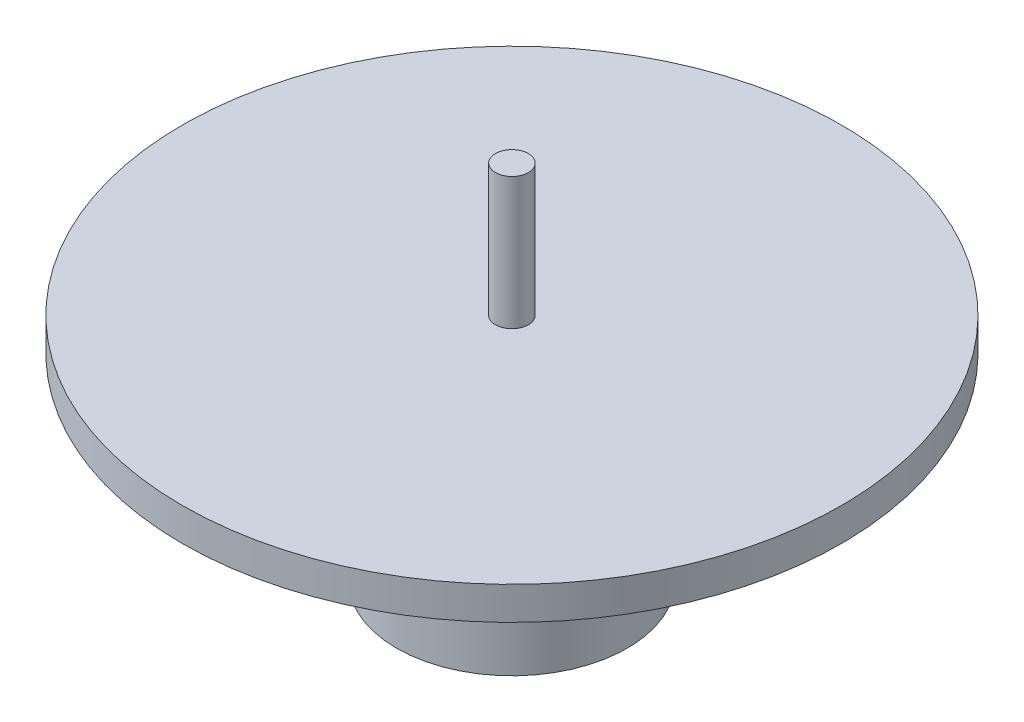
SolidWorks part; units mm, degrees
ref_plane "Plan de face" through (0, 0, 0) normal (0, 0, 1) x (1, 0, 0)
ref_plane "Plan de dessus" through (0, 0, 0) normal (0, 1, 0) x (1, 0, 0)
ref_plane "Plan de droite" through (0, 0, 0) normal (1, 0, 0) x (0, 0, -1)
sketch "Esquisse1" plane through (0, 0, 0) normal (0, 1, 0) x (1, 0, 0)
  circle A0 centre (0, 0) radius 3.5
  dimension "D1" = 7
extrude "Boss.-Extru.1" add sketch "Esquisse1" along normal blind 5
sketch "Esquisse4" plane through (0, 5, 0) normal (0, 1, 0) x (1, 0, 0)
  circle A0 centre (0, 0) radius 5.5
  dimension "D1" = 11
extrude "Boss.-Extru.3" add sketch "Esquisse4" along normal blind 1
sketch "Esquisse5" plane through (0, 6, 0) normal (0, 1, 0) x (1, 0, 0)
  circle A0 centre (0, 0) radius 10
  dimension "D1" = 20
extrude "Boss.-Extru.4" add sketch "Esquisse5" along normal blind 1
sketch "Esquisse6" plane through (0, 7, 0) normal (0, 1, 0) x (1, 0, 0)
  circle A0 centre (0, 0) radius 0.5
  dimension "D1" = 1
extrude "Boss.-Extru.5" add sketch "Esquisse6" along normal blind 4
